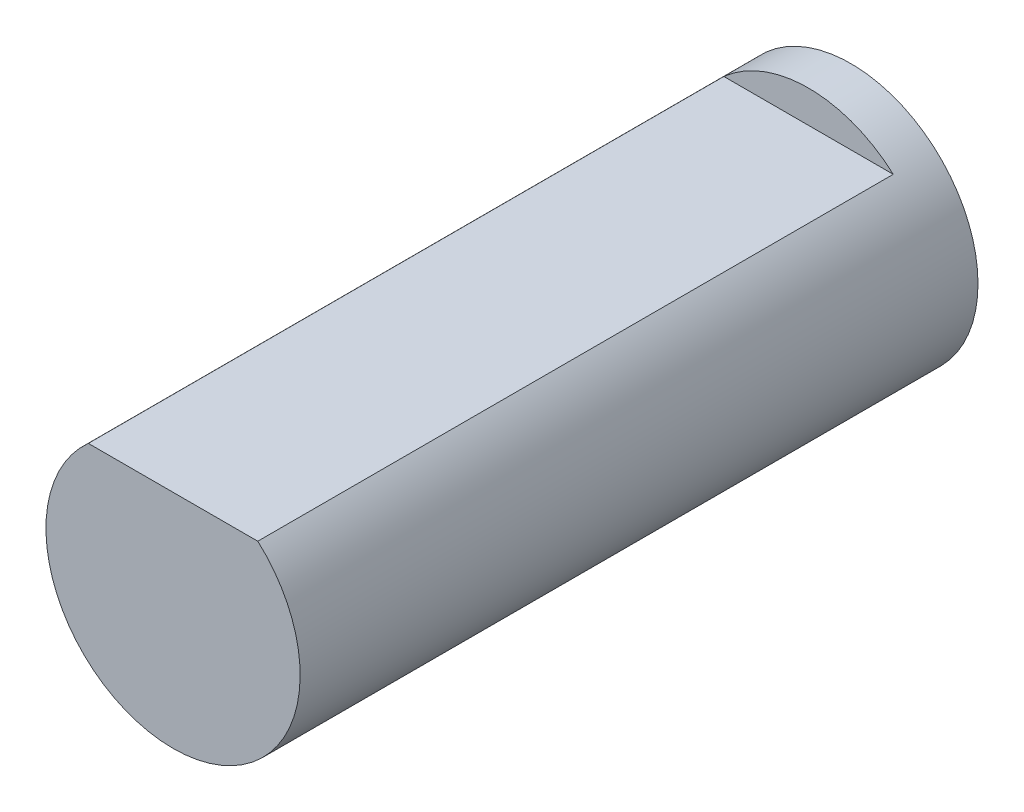
SolidWorks part; units mm, degrees
ref_plane "前视基准面" through (0, 0, 0) normal (0, 0, 1) x (1, 0, 0)
ref_plane "上视基准面" through (0, 0, 0) normal (0, 1, 0) x (1, 0, 0)
ref_plane "右视基准面" through (0, 0, 0) normal (1, 0, 0) x (0, 0, -1)
other "Configuration Table"
sketch "草图1" plane through (0, 0, 0) normal (0, 0, 1) x (1, 0, 0)
  circle A0 centre (0, 0) radius 1.5
  dimension "D1" = 3
extrude "凸台-拉伸1" add sketch "草图1" along normal blind 0.5
sketch "草图2" plane through (0, 0, 0.5) normal (0, 0, 1) x (1, 0, 0)
  line L0 (-1, 1.118) -> (1, 1.118)
  arc A0 (-1, 1.118) -> (1, 1.118) centre (0, 0) ccw
  circle A1 centre (0, 0) radius 1.5 construction
  dimension "D1" = 2
extrude "凸台-拉伸2" add sketch "草图2" along normal blind 7.5
